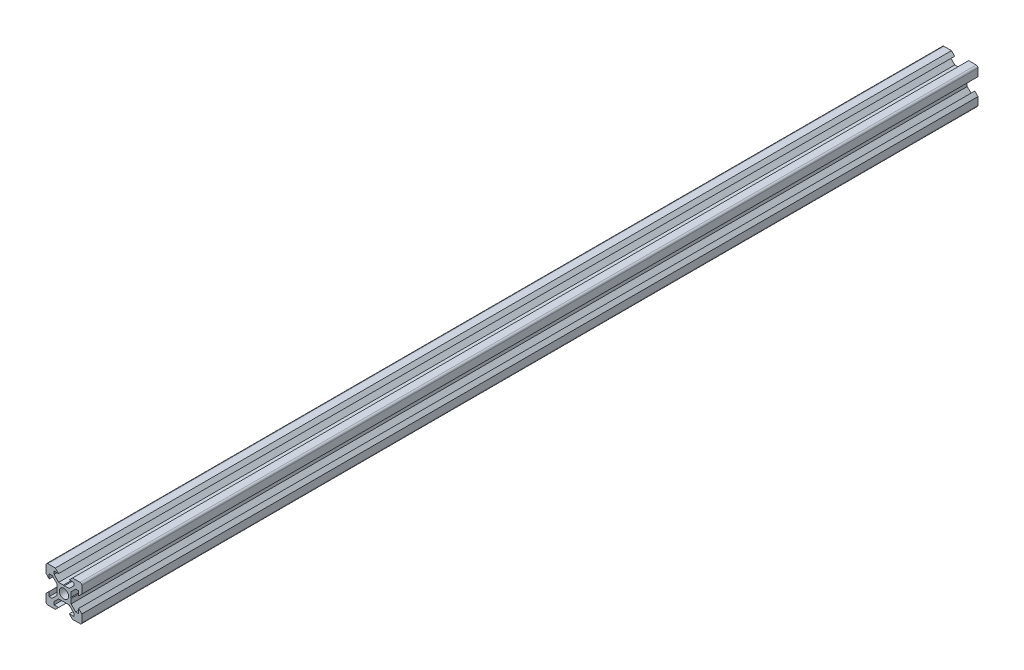
SolidWorks part; units mm, degrees
material "1060-H12 Rod (SS)"
ref_plane "Front Plane" through (0, 0, 0) normal (0, 0, 1) x (1, 0, 0)
ref_plane "Top Plane" through (0, 0, 0) normal (0, 1, 0) x (1, 0, 0)
ref_plane "Right Plane" through (0, 0, 0) normal (1, 0, 0) x (0, 0, -1)
sketch "Sketch1" plane through (0, 0, 0) normal (0, 0, 1) x (1, 0, 0)
  line B0 (10.3368, -8.1134) -> (10.3368, -3.9134)
  line B1 (10.3368, -3.9134) -> (8.5368, -2.1134)
  line B2 (8.5368, -2.1134) -> (8.5368, -4.6134)
  line B3 (8.5368, -4.6134) -> (6.8974, -4.6134)
  line B4 (6.8974, -4.6134) -> (4.3368, -2.0527)
  line B5 (4.3368, -2.0527) -> (4.3368, 0.5866)
  line B6 (4.3368, 0.5866) -> (4.0368, 0.8866)
  line B7 (4.0368, 0.8866) -> (4.3368, 1.1866)
  line B8 (4.3368, 1.1866) -> (4.3368, 3.826)
  line B9 (4.3368, 3.826) -> (6.8974, 6.3866)
  line B10 (6.8974, 6.3866) -> (8.5368, 6.3866)
  line B11 (8.5368, 6.3866) -> (8.5368, 3.8866)
  line B12 (8.5368, 3.8866) -> (10.3368, 5.6866)
  line B13 (10.3368, 5.6866) -> (10.3368, 9.8866)
  line B14 (9.3368, 10.8866) -> (5.1368, 10.8866)
  line B15 (5.1368, 10.8866) -> (3.3368, 9.0866)
  line B16 (3.3368, 9.0866) -> (5.8368, 9.0866)
  line B17 (5.8368, 9.0866) -> (5.8368, 7.4473)
  line B18 (5.8368, 7.4473) -> (3.2761, 4.8866)
  line B19 (3.2761, 4.8866) -> (0.6368, 4.8866)
  line B20 (0.6368, 4.8866) -> (0.3368, 4.5866)
  line B21 (0.3368, 4.5866) -> (0.0368, 4.8866)
  line B22 (0.0368, 4.8866) -> (-2.6026, 4.8866)
  line B23 (-2.6026, 4.8866) -> (-5.1632, 7.4473)
  line B24 (-5.1632, 7.4473) -> (-5.1632, 9.0866)
  line B25 (-5.1632, 9.0866) -> (-2.6632, 9.0866)
  line B26 (-2.6632, 9.0866) -> (-4.4632, 10.8866)
  line B27 (-4.4632, 10.8866) -> (-8.6632, 10.8866)
  line B28 (-9.6632, 9.8866) -> (-9.6632, 5.6866)
  line B29 (-9.6632, 5.6866) -> (-7.8632, 3.8866)
  line B30 (-7.8632, 3.8866) -> (-7.8632, 6.3866)
  line B31 (-7.8632, 6.3866) -> (-6.2239, 6.3866)
  line B32 (-6.2239, 6.3866) -> (-3.6632, 3.826)
  line B33 (-3.6632, 3.826) -> (-3.6632, 1.1866)
  line B34 (-3.6632, 1.1866) -> (-3.3632, 0.8866)
  line B35 (-3.3632, 0.8866) -> (-3.6632, 0.5866)
  line B36 (-3.6632, 0.5866) -> (-3.6632, -2.0527)
  line B37 (-3.6632, -2.0527) -> (-6.2239, -4.6134)
  line B38 (-6.2239, -4.6134) -> (-7.8632, -4.6134)
  line B39 (-7.8632, -4.6134) -> (-7.8632, -2.1134)
  line B40 (-7.8632, -2.1134) -> (-9.6632, -3.9134)
  line B41 (-9.6632, -3.9134) -> (-9.6632, -8.1134)
  line B42 (-8.6632, -9.1134) -> (-4.4632, -9.1134)
  line B43 (-4.4632, -9.1134) -> (-2.6632, -7.3134)
  line B44 (-2.6632, -7.3134) -> (-5.1632, -7.3134)
  line B45 (-5.1632, -7.3134) -> (-5.1632, -5.674)
  line B46 (-5.1632, -5.674) -> (-2.6026, -3.1134)
  line B47 (-2.6026, -3.1134) -> (0.0368, -3.1134)
  line B48 (0.0368, -3.1134) -> (0.3368, -2.8134)
  line B49 (0.3368, -2.8134) -> (0.6368, -3.1134)
  line B50 (0.6368, -3.1134) -> (3.2761, -3.1134)
  line B51 (3.2761, -3.1134) -> (5.8368, -5.674)
  line B52 (5.8368, -5.674) -> (5.8368, -7.3134)
  line B53 (5.8368, -7.3134) -> (3.3368, -7.3134)
  line B54 (3.3368, -7.3134) -> (5.1368, -9.1134)
  line B55 (5.1368, -9.1134) -> (9.3368, -9.1134)
  arc B56 (9.3368, -9.1134) -> (10.3368, -8.1134) centre (9.3368, -8.1134) ccw
  arc B57 (10.3368, 9.8866) -> (9.3368, 10.8866) centre (9.3368, 9.8866) ccw
  arc B58 (-8.6632, 10.8866) -> (-9.6632, 9.8866) centre (-8.6632, 9.8866) ccw
  arc B59 (-9.6632, -8.1134) -> (-8.6632, -9.1134) centre (-8.6632, -8.1134) ccw
  circle B60 centre (0.3368, 0.8866) radius 2.6
sketch_block_instance "AL profile  block  -1"
sketch_block "AL profile  block  " parameters "D1"=3.4331
extrude "Boss-Extrude1" add sketch "Sketch1" along normal blind 500
